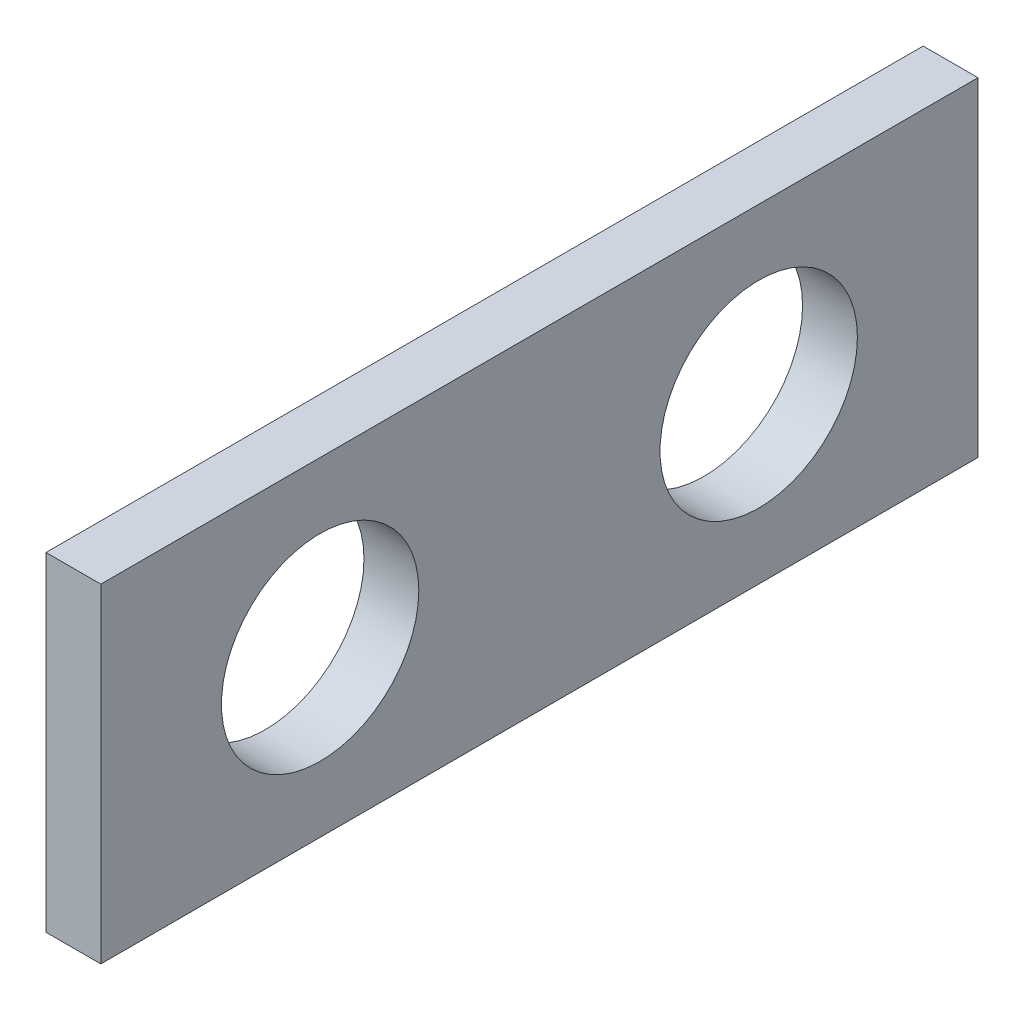
SolidWorks part; units mm, degrees
material "ASTM A36 Steel"
ref_plane "Front Plane" through (0, 0, 0) normal (0, 0, 1) x (1, 0, 0)
ref_plane "Top Plane" through (0, 0, 0) normal (0, 1, 0) x (1, 0, 0)
ref_plane "Right Plane" through (0, 0, 0) normal (1, 0, 0) x (0, 0, -1)
sketch "Sketch1" plane through (0, 0, 0) normal (1, 0, 0) x (0, 0, -1)
  line L1 (-40, -15) -> (40, -15)
  line L2 (-40, -15) -> (-40, 15)
  line L3 (-40, 15) -> (40, 15)
  line L4 (40, -15) -> (40, 15)
  line L5 (-40, -15) -> (40, 15) construction
  line L6 (-40, 15) -> (40, -15) construction
  point P0 (0, 0)
  dimension "D1" = 80
  dimension "D2" = 30
extrude "Boss-Extrude1" add sketch "Sketch1" along normal blind 5
sketch "Sketch2" plane through (5, 0, 0) normal (1, 0, 0) x (0, 0, -1)
  line L0 (40, -15) -> (40, 15) construction
  circle A0 centre (20, 0) radius 9
  circle A1 centre (-20, 0) radius 9
  dimension "D1" = 18
  dimension "D2" = 18
  dimension "D3" = 20
  dimension "D4" = 40
extrude "Cut-Extrude1" cut sketch "Sketch2" against normal blind 5
